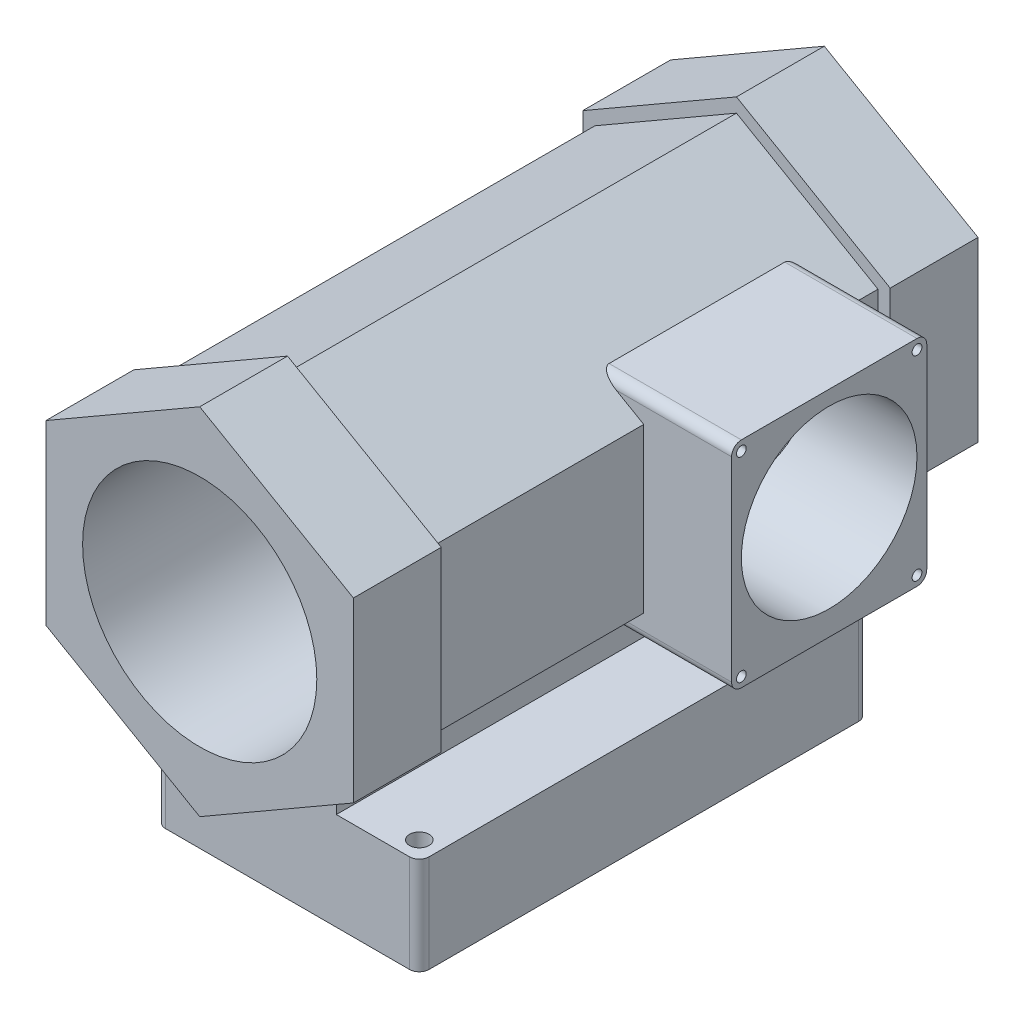
SolidWorks part; units mm, degrees
ref_plane "Спереди" through (0, 0, 0) normal (0, 0, 1) x (1, 0, 0)
ref_plane "Сверху" through (0, 0, 0) normal (0, 1, 0) x (1, 0, 0)
ref_plane "Справа" through (0, 0, 0) normal (1, 0, 0) x (0, 0, -1)
sketch "Эскиз1" plane through (0, 0, 0) normal (0, 0, 1) x (1, 0, 0)
  line L0 (0, 167.4316) -> (0, -321.8926) construction
  line L1 (-50, -200) -> (-50, -138.5641)
  line L2 (0, 167.4316) -> (-145, 83.7158)
  line L3 (-145, 83.7158) -> (-145, -83.7158)
  line L4 (-145, -83.7158) -> (-50, -138.5641)
  line L5 (50, -138.5641) -> (145, -83.7158)
  line L6 (145, -83.7158) -> (145, 83.7158)
  line L7 (135, -300) -> (-135, -300)
  line L8 (-135, -300) -> (-135, -200)
  line L9 (-135, -200) -> (-50, -200)
  line L10 (145, 83.7158) -> (0, 167.4316)
  line L11 (50, -200) -> (50, -138.5641)
  line L12 (135, -200) -> (50, -200)
  line L13 (135, -300) -> (135, -200)
  circle A0 centre (0, 0) radius 145 construction
  point P19 (0, -300)
  dimension "D5" = 290
  dimension "D1" = 300
  dimension "D2" = 100
  dimension "D3" = 270
  dimension "D4" = 100
extrude "Бобышка-Вытянуть1" add sketch "Эскиз1" along normal blind 230
sketch "Эскиз2" plane through (0, 0, 230) normal (0, 0, 1) x (1, 0, 0)
  line L1 (0, 181.8653) -> (-157.5, 90.9327)
  line L2 (-157.5, 90.9327) -> (-157.5, -90.9327)
  line L3 (-157.5, -90.9327) -> (0, -181.8653)
  line L4 (0, -181.8653) -> (157.5, -90.9327)
  line L5 (157.5, -90.9327) -> (157.5, 90.9327)
  line L6 (157.5, 90.9327) -> (0, 181.8653)
  circle A0 centre (0, 0) radius 157.5 construction
  dimension "D1" = 315
extrude "Бобышка-Вытянуть2" add sketch "Эскиз2" along normal blind 90
mirror "Зеркальное отражение1" about plane through (0, 0, 0) normal (0, 0, 1) of bodies 104
sketch "Эскиз4" plane through (0, 0, 320) normal (0, 0, 1) x (1, 0, 0)
  circle A0 centre (0, 0) radius 120
  dimension "D1" = 240
sketch "Эскиз5" plane through (145, 0, 0) normal (1, 0, 0) x (0, 0, -1)
  line L3 (320, -90.9327) -> (320, 90.9327) construction
  line L4 (-10, -110) -> (190, -110)
  line L5 (-10, -110) -> (-10, 110)
  line L6 (-10, 110) -> (190, 110)
  line L7 (190, -110) -> (190, 110)
  line L8 (-10, -110) -> (190, 110) construction
  line L9 (-10, 110) -> (190, -110) construction
  point P6 (90, 0)
  dimension "D1" = 220
  dimension "D2" = 200
  dimension "D3" = 130
extrude "Бобышка-Вытянуть3" add sketch "Эскиз5" along normal blind 90 and the other way blind 145
extrude "Вырез-Вытянуть1" cut sketch "Эскиз4" against normal through all
sketch "Эскиз6" plane through (235, 0, 0) normal (1, 0, 0) x (0, 0, -1)
  line L0 (320, -90.9327) -> (320, 90.9327) construction
  line L1 (-230, -300) -> (230, -300) construction
  circle A0 centre (90, 5) radius 90
  point P0 (90, 5)
  dimension "D3" = 180
  dimension "D1" = 230
  dimension "D2" = 305
extrude "Вырез-Вытянуть2" cut sketch "Эскиз6" against normal up to next
sketch "Эскиз7" plane through (0, -300, 0) normal (0, -1, 0) x (1, 0, 0)
  line L0 (135, 230) -> (135, -230) construction
  line L1 (50, 230) -> (157.5, 230) construction
  line L2 (-135, 230) -> (-135, -230) construction
  line L4 (-135, -230) -> (135, -230) construction
  line L5 (-135, 230) -> (135, 230) construction
  circle A0 centre (115, 210) radius 10
  circle A1 centre (-115, 210) radius 10
  circle A2 centre (115, -210) radius 10
  circle A3 centre (-115, -210) radius 10
  point P16 (-162.7993, -187.4854)
  dimension "D1" = 20
  dimension "D2" = 20
  dimension "D3" = 20
  dimension "D4" = 20
  dimension "D5" = 20
  dimension "D6" = 20
  dimension "D7" = 20
  dimension "D8" = 20
  dimension "D9" = 20
  dimension "D10" = 20
  dimension "D11" = 20
  dimension "D12" = 20
extrude "Вырез-Вытянуть3" cut sketch "Эскиз7" against normal up to next
sketch "Эскиз8" plane through (235, 0, 0) normal (1, 0, 0) x (0, 0, -1)
  line L0 (-10, 110) -> (190, 110) construction
  line L1 (-10, 83.7158) -> (-10, 110) construction
  line L2 (190, -110) -> (190, 110) construction
  line L3 (190, -110) -> (-10, -110) construction
  line L4 (-10, 110) -> (-10, -110) construction
  line L5 (-10, -110) -> (190, -110) construction
  line L6 (190, 110) -> (-10, 110) construction
  circle A0 centre (0, 100) radius 5
  circle A1 centre (0, -100) radius 5
  circle A2 centre (180, 100) radius 5
  circle A3 centre (180, -100) radius 5
  dimension "D1" = 10
  dimension "D2" = 10
  dimension "D3" = 10
  dimension "D4" = 10
  dimension "D5" = 10
  dimension "D6" = 10
  dimension "D7" = 10
  dimension "D8" = 10
  dimension "D9" = 10
  dimension "D10" = 10
  dimension "D11" = 10
  dimension "D12" = 10
extrude "Вырез-Вытянуть4" cut sketch "Эскиз8" against normal blind 30
fillet "Скругление1" radius 10 4 edges at (-135, -250, -230) (-135, -250, 230) (135, -250, 230) (135, -250, -230)
fillet "Скругление2" radius 10 4 edges at (167.2372, -110, 10) (167.2372, -110, -190) (167.2372, 110, 10) (167.2372, 110, -190)
